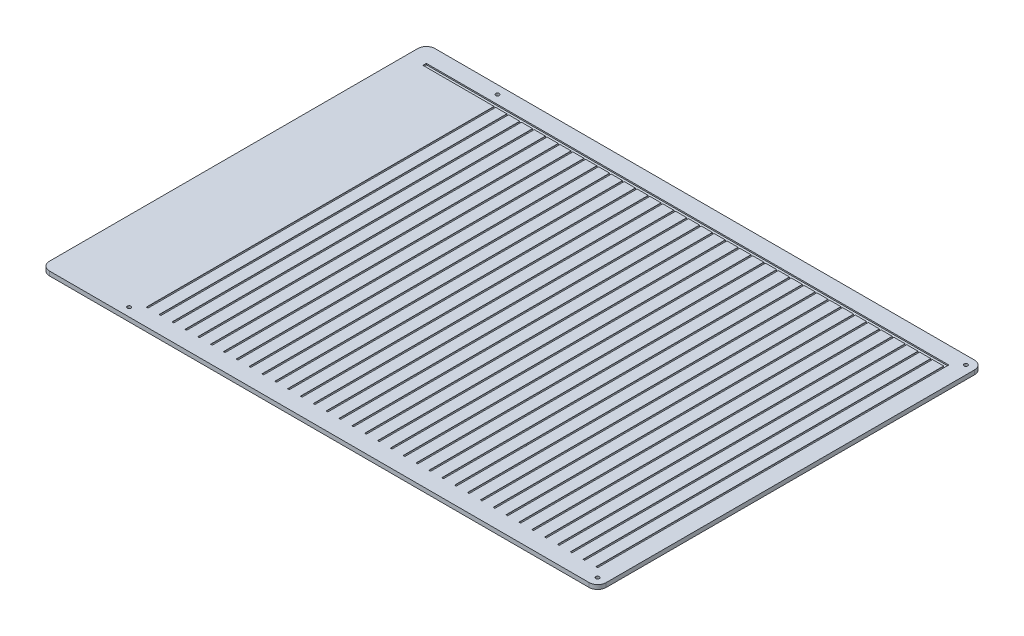
SolidWorks part; units mm, degrees
ref_plane "Front Plane" through (0, 0, 0) normal (0, 0, 1) x (1, 0, 0)
ref_plane "Top Plane" through (0, 0, 0) normal (0, 1, 0) x (1, 0, 0)
ref_plane "Right Plane" through (0, 0, 0) normal (1, 0, 0) x (0, 0, -1)
sketch "Sketch1" plane through (0, 0, 0) normal (0, 1, 0) x (1, 0, 0)
  line L1 (-300, -225) -> (300, -225)
  line L2 (-300, -225) -> (-300, 225) construction
  line L3 (-300, 225) -> (300, 225)
  line L4 (300, -225) -> (300, 225)
  line L5 (-300, -225) -> (300, 225) construction
  line L6 (-300, 225) -> (300, -225) construction
  line L7 (-350, -225) -> (-300, -225)
  line L8 (-350, -225) -> (-350, 225)
  line L9 (-350, 225) -> (-300, 225)
  line L10 (-300, -225) -> (-300, 225) construction
  line L11 (-350, -225) -> (-300, 225) construction
  line L12 (-350, 225) -> (-300, -225) construction
  point P0 (0, 0)
  point P6 (-325, 0)
  dimension "D1" = 450
  dimension "D2" = 600
  dimension "D3" = 50
extrude "Boss-Extrude1" add sketch "Sketch1" along normal blind 5
sketch "Sketch4" plane through (0, 0, 225) normal (0, 0, 1) x (1, 0, 0)
  line L1 (-300, 0) -> (-300, 5) construction
  line L2 (-350, 5) -> (300, 5) construction
  line L4 (280, 5) -> (280, 0) construction
  line L5 (-300, 0) -> (300, 0) construction
  line L6 (300, 5) -> (300, 0) construction
  line L12 (-280, 5) -> (-280, 0) construction
  line L16 (278, 4.5) -> (278, 5)
  line L17 (278, 5) -> (280, 5)
  line L18 (280, 5) -> (280, 4.5)
  line L19 (263, 4.5) -> (263, 5)
  line L20 (263, 5) -> (265, 5)
  line L21 (265, 5) -> (265, 4.5)
  line L22 (278, 4.5) -> (263, 4.5) construction
  line L23 (248, 4.5) -> (248, 5)
  line L24 (248, 5) -> (250, 5)
  line L25 (250, 5) -> (250, 4.5)
  line L26 (233, 4.5) -> (233, 5)
  line L27 (233, 5) -> (235, 5)
  line L28 (235, 5) -> (235, 4.5)
  line L29 (218, 4.5) -> (218, 5)
  line L30 (218, 5) -> (220, 5)
  line L31 (220, 5) -> (220, 4.5)
  line L32 (203, 4.5) -> (203, 5)
  line L33 (203, 5) -> (205, 5)
  line L34 (205, 5) -> (205, 4.5)
  line L35 (188, 4.5) -> (188, 5)
  line L36 (188, 5) -> (190, 5)
  line L37 (190, 5) -> (190, 4.5)
  line L38 (173, 4.5) -> (173, 5)
  line L39 (173, 5) -> (175, 5)
  line L40 (175, 5) -> (175, 4.5)
  line L41 (158, 4.5) -> (158, 5)
  line L42 (158, 5) -> (160, 5)
  line L43 (160, 5) -> (160, 4.5)
  line L44 (143, 4.5) -> (143, 5)
  line L45 (143, 5) -> (145, 5)
  line L46 (145, 5) -> (145, 4.5)
  line L47 (128, 4.5) -> (128, 5)
  line L48 (128, 5) -> (130, 5)
  line L49 (130, 5) -> (130, 4.5)
  line L50 (113, 4.5) -> (113, 5)
  line L51 (113, 5) -> (115, 5)
  line L52 (115, 5) -> (115, 4.5)
  line L53 (98, 4.5) -> (98, 5)
  line L54 (98, 5) -> (100, 5)
  line L55 (100, 5) -> (100, 4.5)
  line L56 (83, 4.5) -> (83, 5)
  line L57 (83, 5) -> (85, 5)
  line L58 (85, 5) -> (85, 4.5)
  line L59 (68, 4.5) -> (68, 5)
  line L60 (68, 5) -> (70, 5)
  line L61 (70, 5) -> (70, 4.5)
  line L62 (53, 4.5) -> (53, 5)
  line L63 (53, 5) -> (55, 5)
  line L64 (55, 5) -> (55, 4.5)
  line L65 (38, 4.5) -> (38, 5)
  line L66 (38, 5) -> (40, 5)
  line L67 (40, 5) -> (40, 4.5)
  line L68 (23, 4.5) -> (23, 5)
  line L69 (23, 5) -> (25, 5)
  line L70 (25, 5) -> (25, 4.5)
  line L71 (8, 4.5) -> (8, 5)
  line L72 (8, 5) -> (10, 5)
  line L73 (10, 5) -> (10, 4.5)
  line L74 (-7, 4.5) -> (-7, 5)
  line L75 (-7, 5) -> (-5, 5)
  line L76 (-5, 5) -> (-5, 4.5)
  line L77 (-22, 4.5) -> (-22, 5)
  line L78 (-22, 5) -> (-20, 5)
  line L79 (-20, 5) -> (-20, 4.5)
  line L80 (-37, 4.5) -> (-37, 5)
  line L81 (-37, 5) -> (-35, 5)
  line L82 (-35, 5) -> (-35, 4.5)
  line L83 (-52, 4.5) -> (-52, 5)
  line L84 (-52, 5) -> (-50, 5)
  line L85 (-50, 5) -> (-50, 4.5)
  line L86 (-67, 4.5) -> (-67, 5)
  line L87 (-67, 5) -> (-65, 5)
  line L88 (-65, 5) -> (-65, 4.5)
  line L89 (-82, 4.5) -> (-82, 5)
  line L90 (-82, 5) -> (-80, 5)
  line L91 (-80, 5) -> (-80, 4.5)
  line L92 (-97, 4.5) -> (-97, 5)
  line L93 (-97, 5) -> (-95, 5)
  line L94 (-95, 5) -> (-95, 4.5)
  line L95 (-112, 4.5) -> (-112, 5)
  line L96 (-112, 5) -> (-110, 5)
  line L97 (-110, 5) -> (-110, 4.5)
  line L98 (-127, 4.5) -> (-127, 5)
  line L99 (-127, 5) -> (-125, 5)
  line L100 (-125, 5) -> (-125, 4.5)
  line L101 (-142, 4.5) -> (-142, 5)
  line L102 (-142, 5) -> (-140, 5)
  line L103 (-140, 5) -> (-140, 4.5)
  line L104 (-157, 4.5) -> (-157, 5)
  line L105 (-157, 5) -> (-155, 5)
  line L106 (-155, 5) -> (-155, 4.5)
  line L107 (-172, 4.5) -> (-172, 5)
  line L108 (-172, 5) -> (-170, 5)
  line L109 (-170, 5) -> (-170, 4.5)
  line L110 (-187, 4.5) -> (-187, 5)
  line L111 (-187, 5) -> (-185, 5)
  line L112 (-185, 5) -> (-185, 4.5)
  line L113 (-202, 4.5) -> (-202, 5)
  line L114 (-202, 5) -> (-200, 5)
  line L115 (-200, 5) -> (-200, 4.5)
  line L116 (-217, 4.5) -> (-217, 5)
  line L117 (-217, 5) -> (-215, 5)
  line L118 (-215, 5) -> (-215, 4.5)
  line L119 (-232, 4.5) -> (-232, 5)
  line L120 (-232, 5) -> (-230, 5)
  line L121 (-230, 5) -> (-230, 4.5)
  line L122 (-247, 4.5) -> (-247, 5)
  line L123 (-247, 5) -> (-245, 5)
  line L124 (-245, 5) -> (-245, 4.5)
  arc A3 (278, 4.5) -> (280, 4.5) centre (279, 4.5) ccw
  arc A4 (263, 4.5) -> (265, 4.5) centre (264, 4.5) ccw
  arc A5 (248, 4.5) -> (250, 4.5) centre (249, 4.5) ccw
  arc A6 (233, 4.5) -> (235, 4.5) centre (234, 4.5) ccw
  arc A7 (218, 4.5) -> (220, 4.5) centre (219, 4.5) ccw
  arc A8 (203, 4.5) -> (205, 4.5) centre (204, 4.5) ccw
  arc A9 (188, 4.5) -> (190, 4.5) centre (189, 4.5) ccw
  arc A10 (173, 4.5) -> (175, 4.5) centre (174, 4.5) ccw
  arc A11 (158, 4.5) -> (160, 4.5) centre (159, 4.5) ccw
  arc A12 (143, 4.5) -> (145, 4.5) centre (144, 4.5) ccw
  arc A13 (128, 4.5) -> (130, 4.5) centre (129, 4.5) ccw
  arc A14 (113, 4.5) -> (115, 4.5) centre (114, 4.5) ccw
  arc A15 (98, 4.5) -> (100, 4.5) centre (99, 4.5) ccw
  arc A16 (83, 4.5) -> (85, 4.5) centre (84, 4.5) ccw
  arc A17 (68, 4.5) -> (70, 4.5) centre (69, 4.5) ccw
  arc A18 (53, 4.5) -> (55, 4.5) centre (54, 4.5) ccw
  arc A19 (38, 4.5) -> (40, 4.5) centre (39, 4.5) ccw
  arc A20 (23, 4.5) -> (25, 4.5) centre (24, 4.5) ccw
  arc A21 (8, 4.5) -> (10, 4.5) centre (9, 4.5) ccw
  arc A22 (-7, 4.5) -> (-5, 4.5) centre (-6, 4.5) ccw
  arc A23 (-22, 4.5) -> (-20, 4.5) centre (-21, 4.5) ccw
  arc A24 (-37, 4.5) -> (-35, 4.5) centre (-36, 4.5) ccw
  arc A25 (-52, 4.5) -> (-50, 4.5) centre (-51, 4.5) ccw
  arc A26 (-67, 4.5) -> (-65, 4.5) centre (-66, 4.5) ccw
  arc A27 (-82, 4.5) -> (-80, 4.5) centre (-81, 4.5) ccw
  arc A28 (-97, 4.5) -> (-95, 4.5) centre (-96, 4.5) ccw
  arc A29 (-112, 4.5) -> (-110, 4.5) centre (-111, 4.5) ccw
  arc A30 (-127, 4.5) -> (-125, 4.5) centre (-126, 4.5) ccw
  arc A31 (-142, 4.5) -> (-140, 4.5) centre (-141, 4.5) ccw
  arc A32 (-157, 4.5) -> (-155, 4.5) centre (-156, 4.5) ccw
  arc A33 (-172, 4.5) -> (-170, 4.5) centre (-171, 4.5) ccw
  arc A34 (-187, 4.5) -> (-185, 4.5) centre (-186, 4.5) ccw
  arc A35 (-202, 4.5) -> (-200, 4.5) centre (-201, 4.5) ccw
  arc A36 (-217, 4.5) -> (-215, 4.5) centre (-216, 4.5) ccw
  arc A37 (-232, 4.5) -> (-230, 4.5) centre (-231, 4.5) ccw
  arc A38 (-247, 4.5) -> (-245, 4.5) centre (-246, 4.5) ccw
  point P0 (-300, 0)
  dimension "D4" = 1
  dimension "D2" = 20
  dimension "D1" = 20
  dimension "D6" = 15
  dimension "D5" = 36
extrude "Cut-Extrude2" cut sketch "Sketch4" against normal offset from surface (410 mm away) 20 from offset 20 up to face at (-25, 2.5, -225) offset against normal yes
sketch "Sketch6" plane through (280, 0, 0) normal (-1, 0, 0) x (0, 0, 1)
  line L0 (-205, 5) -> (-201, 5)
  line L1 (-205, 5) -> (205, 5) construction
  line L2 (-201, 5) -> (-201, 3.5)
  line L4 (-205, 5) -> (-205, 3.5)
  line L6 (-201, 3.5) -> (-205, 3.5)
  line L7 (-205, 3.5) -> (-205, 4.5) construction
  line L8 (-205, 3.5) -> (-205, 4.5)
  point P8 (0, 0)
  line M4 (-205, 5) -> (-205, 4.5)
  line M5 (-205, 4.5) -> (205, 4.5)
  line M7 (205, 5) -> (-205, 5)
  dimension "D1" = 4
extrude "Cut-Extrude3" cut sketch "Sketch6" along normal offset from surface (610 mm away) 20 contours L6 L2 L4 M5 | L2 M7 M4 M5 up to face at (-350, 2.5, 0)
sketch "Sketch9" plane through (0, 5, 0) normal (0, 1, 0) x (1, 0, 0)
  line L0 (280, 205) -> (300, 225) construction
  line L1 (-247, 205) -> (-267, 225) construction
  line L2 (-330, 205) -> (280, 205) construction
  line L3 (300, 225) -> (-350, 225) construction
  line L4 (-247, 201) -> (-247, -205) construction
  line L5 (-247, -205) -> (-267, -225) construction
  line L6 (-350, -225) -> (300, -225) construction
  line L7 (280, -205) -> (300, -225) construction
  point P4 (290, 215)
  point P12 (-257, 215)
  point P18 (-257, -215)
  point P21 (290, -215)
  dimension "D1" = 45
  dimension "D2" = 45
hole_wizard "Tap Drill for M5x0.8 Tap2" positions "3DSketch4" profile "Sketch13" hole size "M5x0.8" standard "ANSI Metric" end condition through all
sketch3d "3DSketch4"
  point P0 (290, 5, -215)
  point P3 (290, 5, 215)
  point P6 (-257, 5, 215)
  point P9 (-257, 5, -215)
sketch "Sketch13" plane through (290, 5, -215) normal (1, 0, 0) x (0, 0, 1)
  line L0 (0, 0) -> (0, 5)
  line L1 (0, 5) -> (2.1, 5)
  line L2 (2.1, 5) -> (2.1, 0)
  line L5 (2.1, 0) -> (0, 0)
  line L11 (0, -6.35) -> (0, 107.95) construction
  dimension "Thru Hole Dia." = 4.2
  dimension "Thru Hole Depth" = 5
fillet "Fillet2" radius 10 4 edges at (300, 2.5, -225) (300, 2.5, 225) (-350, 2.5, -225) (-350, 2.5, 225)
equation "\"half_plate_thickness\"= 0.5cm'Total plate thickness = 1 cm"
equation "\"plate_length\"= 60cm'Parallel to x-axis"
equation "\"plate_width\"= 45cm'Parallel to z-axis"
equation "\"D1@Sketch1\"=\"plate_width\""
equation "\"D2@Sketch1\"=\"plate_length\""
equation "\"D1@Boss-Extrude1\"=\"half_plate_thickness\""
equation "\"electronics_box_length\"= 5cm'Parallel to x-axis"
equation "\"D3@Sketch1\"=\"electronics_box_length\""
equation "\"wall_width\"= 2cm'Same value for wall_length"
equation "\"eds_radius\"= 1mm"
equation "\"D2@Sketch4\"=\"wall_width\""
equation "\"eds_spacing\"= 15mm"
equation "\"general_tolerance\"= 0.5mm"
equation "\"D1@Sketch4\"=\"wall_width\""
equation "\"D3@Sketch4\"=\"general_tolerance\""
equation "\"D4@Sketch4\"=\"eds_radius\""
equation "\"D6@Sketch4\"=\"eds_spacing\""
equation "\"eds_count\" = 36"
equation "\"D5@Sketch4\"=\"eds_count\""
equation "\"D19@Cut-Extrude2\"=\"wall_width\""
equation "\"D1@Cut-Extrude2\"=\"wall_width\""
equation "\"D1@Sketch6\"=\"eds_radius\"*4"
equation "\"D1@Cut-Extrude3\"=\"wall_width\""
equation "\"plate_fillet_radius\"= 10mm"
equation "\"D1@Fillet2\"=\"plate_fillet_radius\""
